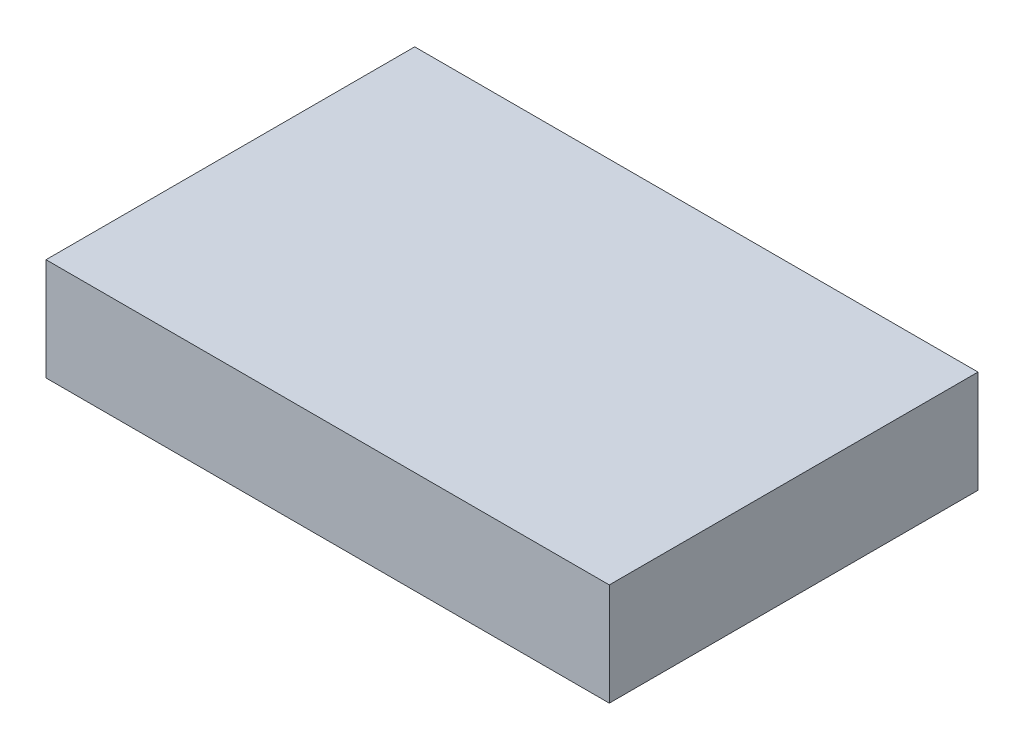
SolidWorks part; units mm, degrees
ref_plane "前视基准面" through (0, 0, 0) normal (0, 0, 1) x (1, 0, 0)
ref_plane "上视基准面" through (0, 0, 0) normal (0, 1, 0) x (1, 0, 0)
ref_plane "右视基准面" through (0, 0, 0) normal (1, 0, 0) x (0, 0, -1)
sketch "Sketch1" plane through (0, 0, 0) normal (0, 1, 0) x (1, 0, 0)
  line L1 (-55, 36) -> (55, 36)
  line L2 (-55, 36) -> (-55, -36)
  line L3 (-55, -36) -> (55, -36)
  line L4 (55, 36) -> (55, -36)
  line L5 (0, -36) -> (0, 36) construction
  line L6 (-55, 0) -> (55, 0) construction
  point P0 (0, 0)
  dimension "D1" = 110
  dimension "D2" = 72
extrude "Boss-Extrude1" add sketch "Sketch1" along normal blind 20
